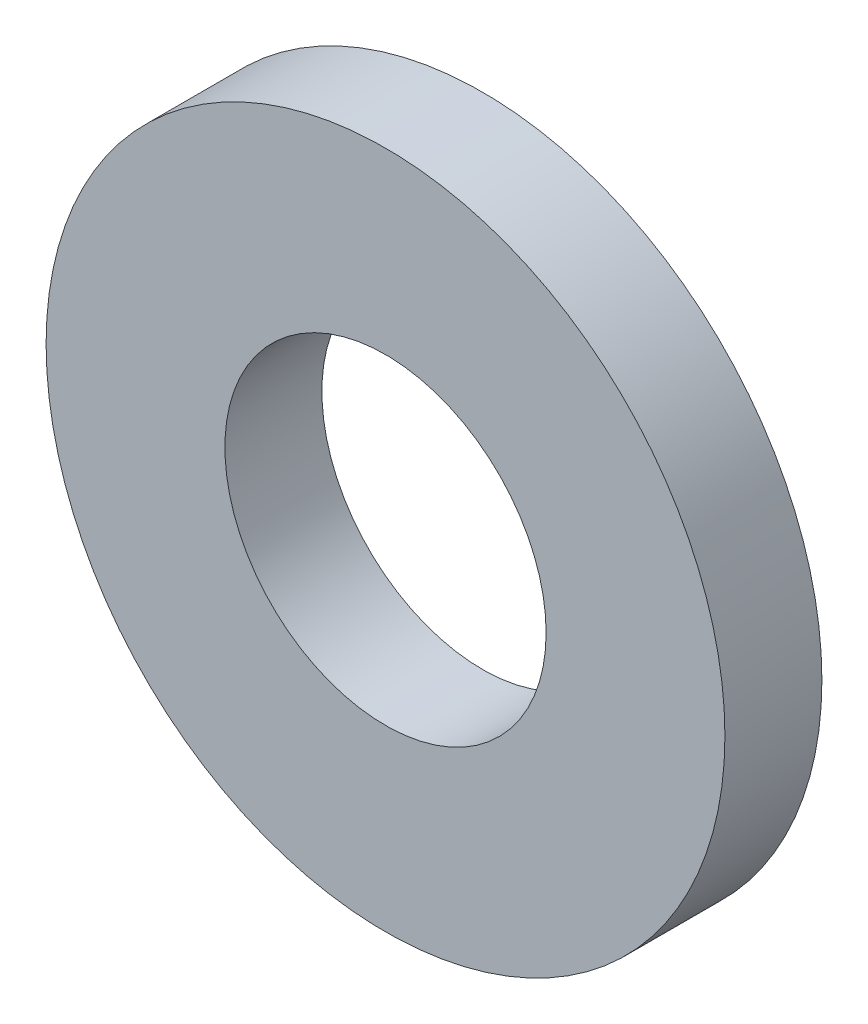
SolidWorks part; units mm, degrees
material "ПК/АБС"
ref_plane "Спереди(Плоскость XY)" through (0, 0, 0) normal (0, 0, 1) x (1, 0, 0)
ref_plane "Сверху(Плоскость XZ)" through (0, 0, 0) normal (0, 1, 0) x (1, 0, 0)
ref_plane "Справа(Плоскость ZY)" through (0, 0, 0) normal (1, 0, 0) x (0, 0, -1)
sketch "Эскиз1" plane through (0, 0, 0) normal (0, 0, 1) x (1, 0, 0)
  circle A0 centre (0, 0) radius 2.8
  circle A1 centre (0, 0) radius 1.325
  dimension "D1" = 2.65
  dimension "D2" = 5.6
extrude "Бобышка-Вытянуть1" add sketch "Эскиз1" along normal blind 0.8
